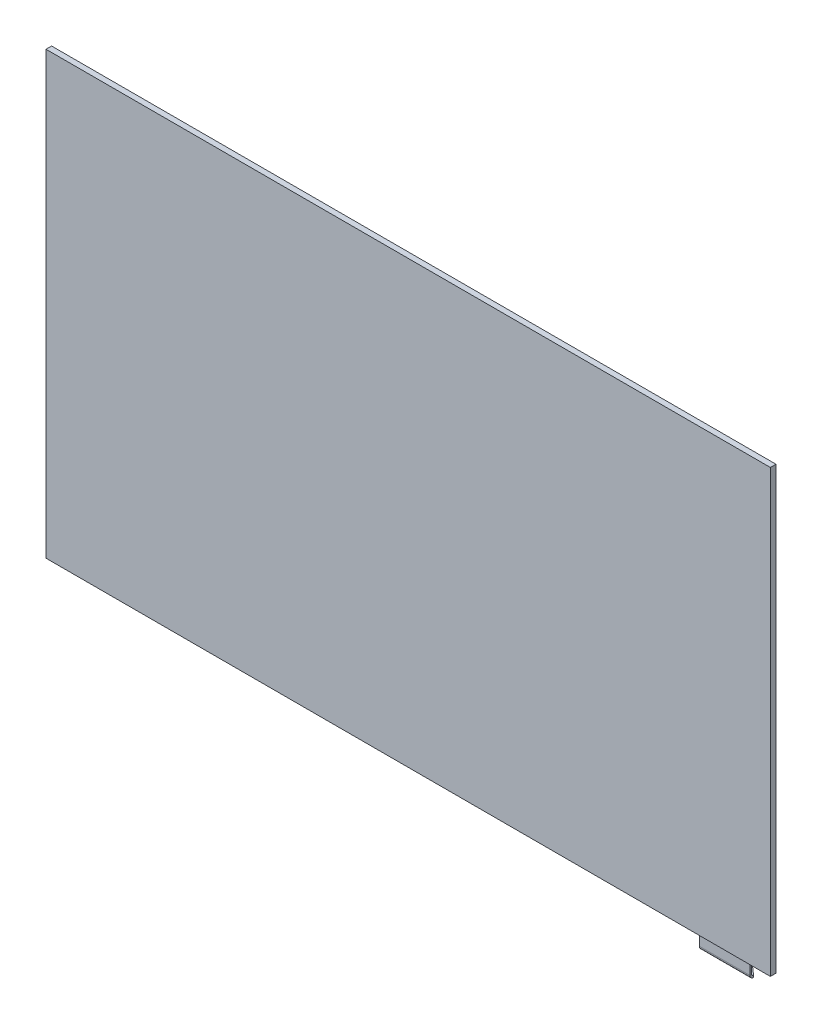
SolidWorks part; units mm, degrees
ref_plane "Front Plane" through (0, 0, 0) normal (0, 0, 1) x (1, 0, 0)
ref_plane "Top Plane" through (0, 0, 0) normal (0, 1, 0) x (1, 0, 0)
ref_plane "Right Plane" through (0, 0, 0) normal (1, 0, 0) x (0, 0, -1)
sketch "Sketch1" plane through (0, 0, 0) normal (0, 0, 1) x (1, 0, 0)
  line L1 (-102.3937, -62.3094) -> (102.3938, -62.3094)
  line L2 (-102.3937, -62.3094) -> (-102.3937, 62.3094)
  line L3 (-102.3937, 62.3094) -> (102.3938, 62.3094)
  line L4 (102.3938, -62.3094) -> (102.3938, 62.3094)
  line L5 (-102.3937, -62.3094) -> (102.3938, 62.3094) construction
  line L6 (-102.3937, 62.3094) -> (102.3938, -62.3094) construction
  point P0 (0, 0)
  dimension "D1" = 204.7875
  dimension "D2" = 124.6188
extrude "Boss-Extrude1" add sketch "Sketch1" along normal blind 1.5875
ref_plane "Plane1" through (96.0438, 0, 0) normal (1, 0, 0) x (0, 0, -1)
sketch "Sketch2" plane through (96.0438, 0, 0) normal (1, 0, 0) x (0, 0, -1)
  line L0 (-0.7937, -62.3094) -> (-0.7937, -65.4844)
  line L1 (-1.5875, -62.3094) -> (0, -62.3094) construction
  line L2 (0, -66.2781) -> (4.2227, -66.2781)
  line L3 (5.0165, -65.4844) -> (5.0165, -27.3844)
  line L4 (0, 68.5403) -> (0, -68.5403) construction
  arc A0 (-0.7937, -65.4844) -> (0, -66.2781) centre (0, -65.4844) ccw
  arc A1 (4.2227, -66.2781) -> (5.0165, -65.4844) centre (4.2227, -65.4844) ccw
  dimension "D1" = 5.8102
  dimension "D2" = 3.175
  dimension "D3" = 38.1
extrude "Extrude-Thin1" add sketch "Sketch2" against normal blind 14.2875 thin thin type mid plane wall 0.508
sketch "Sketch3" plane through (0, -66.5321, 0) normal (0, -1, 0) x (1, 0, 0)
  line L0 (88.9, 1.0477) -> (88.9, -8.3052) construction
  line L1 (81.7563, 1.0477) -> (96.0438, 1.0477) construction
  line L2 (81.7563, 0) -> (86.5188, -4.2228)
  line L3 (81.7563, -4.2228) -> (96.0438, -4.2228) construction
  line L4 (86.5188, -4.2228) -> (86.5188, -5.2705)
  line L5 (81.7563, -5.2705) -> (96.0438, -5.2705) construction
  line L6 (86.5188, -5.2705) -> (81.7563, -5.2705)
  line L7 (81.7563, -5.2705) -> (81.7563, 0)
  line L8 (91.2813, -4.2228) -> (91.2813, -5.2705)
  line L9 (96.0438, 0) -> (91.2813, -4.2228)
  line L10 (91.2813, -5.2705) -> (96.0438, -5.2705)
  line L11 (96.0438, -5.2705) -> (96.0438, 0)
  dimension "D1" = 4.7625
extrude "Cut-Extrude1" cut sketch "Sketch3" against normal through all
